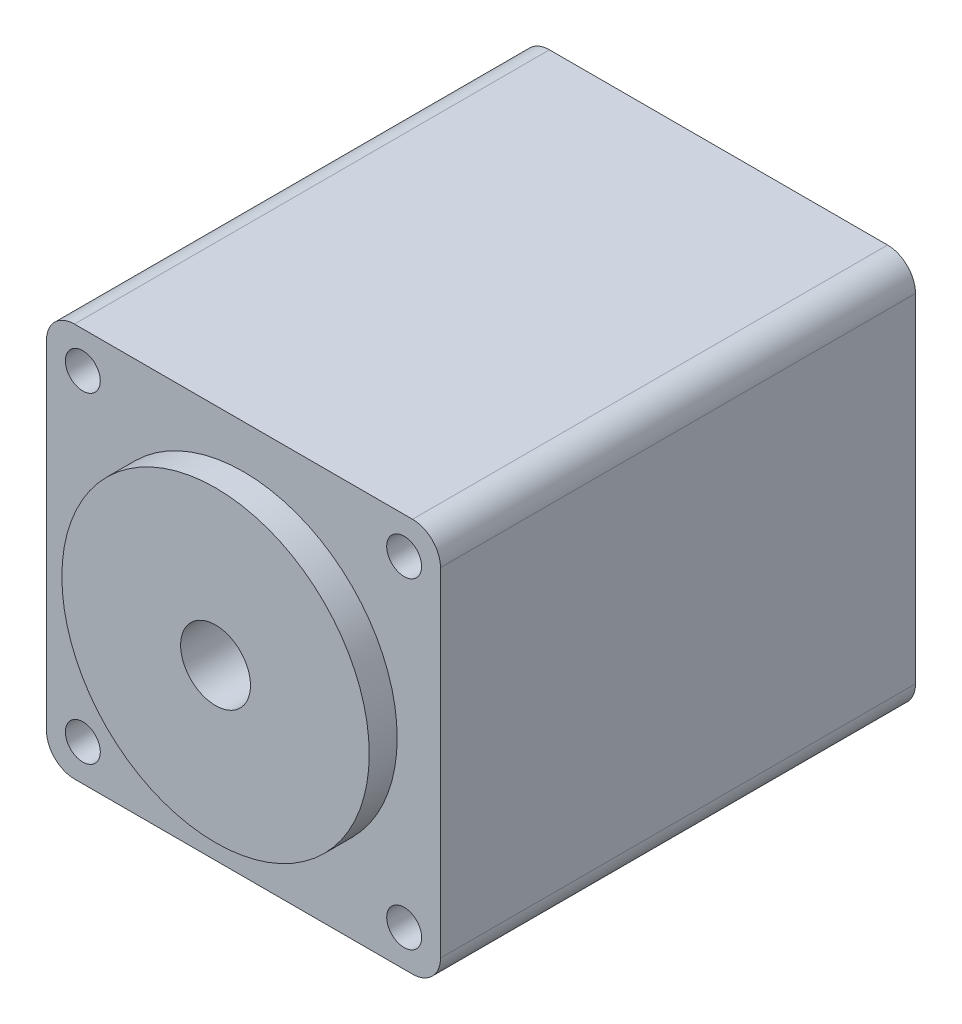
SolidWorks part; units mm, degrees
ref_plane "Front Plane" through (0, 0, 0) normal (0, 0, 1) x (1, 0, 0)
ref_plane "Top Plane" through (0, 0, 0) normal (0, 1, 0) x (1, 0, 0)
ref_plane "Right Plane" through (0, 0, 0) normal (1, 0, 0) x (0, 0, -1)
sketch "Sketch1" plane through (0, 0, 0) normal (0, 0, 1) x (1, 0, 0)
  line L1 (-12.1, 14.1) -> (12.1, 14.1)
  line L2 (-14.1, 12.1) -> (-14.1, -12.1)
  line L3 (-12.1, -14.1) -> (12.1, -14.1)
  line L4 (14.1, 12.1) -> (14.1, -12.1)
  arc A0 (-14.1, -12.1) -> (-12.1, -14.1) centre (-12.1, -12.1) ccw
  arc A1 (12.1, -14.1) -> (14.1, -12.1) centre (12.1, -12.1) ccw
  arc A2 (12.1, 14.1) -> (14.1, 12.1) centre (12.1, 12.1) cw
  arc A3 (-12.1, 14.1) -> (-14.1, 12.1) centre (-12.1, 12.1) ccw
  point P4 (0, 14.1)
  point P6 (-14.1, 0)
  point P9 (-14.1, -14.1)
  point P14 (14.1, 14.1)
  point P17 (-14.1, 14.1)
  dimension "D3" = 2
  dimension "D1" = 28.2
  dimension "D2" = 28.2
extrude "Boss-Extrude1" add sketch "Sketch1" along normal blind 34
sketch "Sketch2" plane through (0, 0, 34) normal (0, 0, 1) x (1, 0, 0)
  circle A0 centre (0, 0) radius 11
  dimension "D1" = 22
extrude "Boss-Extrude2" add sketch "Sketch2" along normal blind 2
sketch "Sketch3" plane through (0, 0, 36) normal (0, 0, 1) x (1, 0, 0)
  circle A0 centre (0, 0) radius 2.5
  dimension "D1" = 5
extrude "Cut-Extrude1" cut sketch "Sketch3" against normal blind 10
sketch "Sketch4" plane through (0, 0, 34) normal (0, 0, 1) x (1, 0, 0)
  line L0 (15.51, 0) -> (-15.51, 0) construction
  circle A0 centre (-11.5, 11.5) radius 1.25
  circle A1 centre (11.5, 11.5) radius 1.25
  circle A2 centre (11.5, -11.5) radius 1.25
  circle A3 centre (-11.5, -11.5) radius 1.25
  dimension "D1" = 2.5
  dimension "D2" = 23
  dimension "D3" = 11.5
  dimension "D4" = 11.5
extrude "Cut-Extrude2" cut sketch "Sketch4" against normal blind 10
